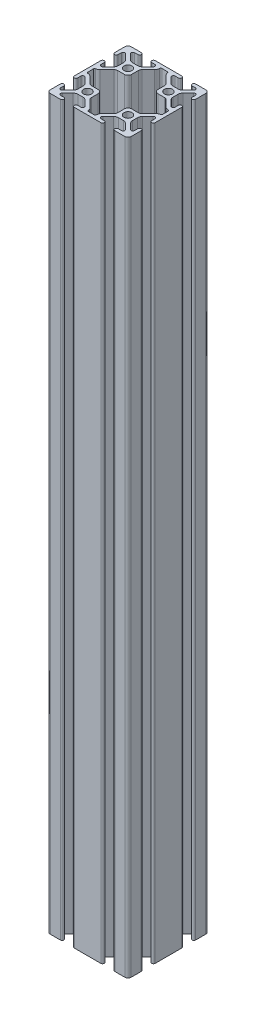
SolidWorks part; units mm, degrees
material "6061-T6 (SS)"
ref_plane "Front Plane" through (0, 0, 0) normal (0, 0, 1) x (1, 0, 0)
ref_plane "Top Plane" through (0, 0, 0) normal (0, 1, 0) x (1, 0, 0)
ref_plane "Right Plane" through (0, 0, 0) normal (1, 0, 0) x (0, 0, -1)
sketch "Sketch1" plane through (0, 0, 0) normal (0, 0, 1) x (1, 0, 0)
  line L0 (0, 0) -> (0, 450)
  dimension "D1" = 450
other "25 series extrusions 25-5050(1)"
ref_plane "Plane1" through (0, 0, 0) normal (0, 1, 0) x (-1, 0, 0)
sketch "Sketch13" plane through (0, 0, 0) normal (0, 1, 0) x (-1, 0, 0)
  line L0 (1.94, -22.8664) -> (-1.461, -22.8664)
  line L1 (-3.1194, -20.3719) -> (-7.4717, -16.0197)
  line L2 (-8.1189, -14.4571) -> (-8.1189, -10.3287)
  line L3 (-10.3287, -8.1189) -> (-14.4571, -8.1189)
  line L4 (-16.0197, -7.4717) -> (-19.8593, -3.632)
  line L5 (-22.8664, -1.94) -> (-22.8664, 1.461)
  line L6 (-20.3719, 3.1194) -> (-16.0197, 7.4717)
  line L7 (-14.4571, 8.1189) -> (-10.3287, 8.1189)
  line L8 (-8.1189, 10.3287) -> (-8.1189, 14.4571)
  line L9 (-7.4717, 16.0197) -> (-3.632, 19.8593)
  line L10 (-1.94, 22.8664) -> (1.461, 22.8664)
  line L11 (3.1194, 20.3719) -> (7.4717, 16.0197)
  line L12 (8.1189, 14.4571) -> (8.1189, 10.3287)
  line L13 (10.3287, 8.1189) -> (14.4571, 8.1189)
  line L14 (16.0197, 7.4717) -> (19.8593, 3.632)
  line L15 (22.8664, 1.94) -> (22.8664, -1.461)
  line L16 (20.3719, -3.1194) -> (16.0197, -7.4717)
  line L17 (14.4571, -8.1189) -> (10.3287, -8.1189)
  line L18 (8.1189, -10.3287) -> (8.1189, -14.4571)
  line L19 (7.4717, -16.0197) -> (3.632, -19.8593)
  line L20 (16.815, -25) -> (23, -25)
  line L21 (25, -23) -> (25, -16.815)
  line L22 (22.87, -16.815) -> (22.87, -18.7728)
  line L23 (21.0396, -19.531) -> (17.811, -16.3024)
  line L24 (16.8811, -14.0573) -> (16.8811, -10.9427)
  line L25 (17.811, -8.6976) -> (21.0396, -5.469)
  line L26 (22.87, -6.2272) -> (22.87, -8.185)
  line L27 (25, -8.185) -> (25, 8.185)
  line L28 (22.87, 8.185) -> (22.87, 6.2272)
  line L29 (21.0396, 5.469) -> (17.811, 8.6976)
  line L30 (16.8811, 10.9427) -> (16.8811, 14.0573)
  line L31 (17.811, 16.3024) -> (21.0396, 19.531)
  line L32 (22.87, 18.7728) -> (22.87, 16.815)
  line L33 (25, 16.815) -> (25, 23)
  line L34 (23, 25) -> (16.815, 25)
  line L35 (16.815, 22.87) -> (18.7728, 22.87)
  line L36 (19.531, 21.0396) -> (16.3024, 17.811)
  line L37 (14.0573, 16.8811) -> (10.9427, 16.8811)
  line L38 (8.6976, 17.811) -> (5.469, 21.0396)
  line L39 (6.2272, 22.87) -> (8.185, 22.87)
  line L40 (8.185, 25) -> (-8.185, 25)
  line L41 (-8.185, 22.87) -> (-6.2272, 22.87)
  line L42 (-5.469, 21.0396) -> (-8.6976, 17.811)
  line L43 (-10.9427, 16.8811) -> (-14.0573, 16.8811)
  line L44 (-16.3024, 17.811) -> (-19.531, 21.0396)
  line L45 (-18.7728, 22.87) -> (-16.815, 22.87)
  line L46 (-16.815, 25) -> (-23, 25)
  line L47 (-25, 23) -> (-25, 16.815)
  line L48 (-22.87, 16.815) -> (-22.87, 18.7728)
  line L49 (-21.0396, 19.531) -> (-17.811, 16.3024)
  line L50 (-16.8811, 14.0573) -> (-16.8811, 10.9427)
  line L51 (-17.811, 8.6976) -> (-21.0396, 5.469)
  line L52 (-22.87, 6.2272) -> (-22.87, 8.185)
  line L53 (-25, 8.185) -> (-25, -8.185)
  line L54 (-22.87, -8.185) -> (-22.87, -6.2272)
  line L55 (-21.0396, -5.469) -> (-17.811, -8.6976)
  line L56 (-16.8811, -10.9427) -> (-16.8811, -14.0573)
  line L57 (-17.811, -16.3024) -> (-21.0396, -19.531)
  line L58 (-22.87, -18.7728) -> (-22.87, -16.815)
  line L59 (-25, -16.815) -> (-25, -23)
  line L60 (-23, -25) -> (-16.815, -25)
  line L61 (-16.815, -22.87) -> (-18.7728, -22.87)
  line L62 (-19.531, -21.0396) -> (-16.3024, -17.811)
  line L63 (-14.0573, -16.8811) -> (-10.9427, -16.8811)
  line L64 (-8.6976, -17.811) -> (-5.469, -21.0396)
  line L65 (-6.2272, -22.87) -> (-8.185, -22.87)
  line L66 (-8.185, -25) -> (8.185, -25)
  line L67 (8.185, -22.87) -> (6.2272, -22.87)
  line L68 (5.469, -21.0396) -> (8.6976, -17.811)
  line L69 (10.9427, -16.8811) -> (14.0573, -16.8811)
  line L70 (16.3024, -17.811) -> (19.531, -21.0396)
  line L71 (18.7728, -22.87) -> (16.815, -22.87)
  circle A0 centre (12.5, 12.5) radius 2.5
  circle A1 centre (-12.5, -12.5) radius 2.5
  circle A2 centre (12.5, -12.5) radius 2.5
  circle A3 centre (-12.5, 12.5) radius 2.5
  arc A4 (1.94, -22.8664) -> (2.702, -22.1044) centre (1.94, -22.1044) ccw
  arc A5 (-2.2165, -22.2036) -> (-1.461, -22.8664) centre (-1.461, -22.1044) ccw
  arc A6 (-2.2165, -22.2036) -> (-3.1194, -20.3719) centre (-5.3645, -22.617) ccw
  arc A7 (-8.1189, -14.4571) -> (-7.4717, -16.0197) centre (-5.9091, -14.4571) ccw
  arc A8 (-8.1189, -10.3287) -> (-10.3287, -8.1189) centre (-10.3287, -10.3287) ccw
  arc A9 (-16.0197, -7.4717) -> (-14.4571, -8.1189) centre (-14.4571, -5.9091) ccw
  arc A10 (-19.8593, -3.632) -> (-22.1044, -2.702) centre (-22.1044, -5.877) ccw
  arc A11 (-22.8664, -1.94) -> (-22.1044, -2.702) centre (-22.1044, -1.94) ccw
  arc A12 (-22.2036, 2.2165) -> (-22.8664, 1.461) centre (-22.1044, 1.461) ccw
  arc A13 (-22.2036, 2.2165) -> (-20.3719, 3.1194) centre (-22.617, 5.3645) ccw
  arc A14 (-14.4571, 8.1189) -> (-16.0197, 7.4717) centre (-14.4571, 5.9091) ccw
  arc A15 (-10.3287, 8.1189) -> (-8.1189, 10.3287) centre (-10.3287, 10.3287) ccw
  arc A16 (-7.4717, 16.0197) -> (-8.1189, 14.4571) centre (-5.9091, 14.4571) ccw
  arc A17 (-3.632, 19.8593) -> (-2.702, 22.1044) centre (-5.877, 22.1044) ccw
  arc A18 (-1.94, 22.8664) -> (-2.702, 22.1044) centre (-1.94, 22.1044) ccw
  arc A19 (2.2165, 22.2036) -> (1.461, 22.8664) centre (1.461, 22.1044) ccw
  arc A20 (2.2165, 22.2036) -> (3.1194, 20.3719) centre (5.3645, 22.617) ccw
  arc A21 (8.1189, 14.4571) -> (7.4717, 16.0197) centre (5.9091, 14.4571) ccw
  arc A22 (8.1189, 10.3287) -> (10.3287, 8.1189) centre (10.3287, 10.3287) ccw
  arc A23 (16.0197, 7.4717) -> (14.4571, 8.1189) centre (14.4571, 5.9091) ccw
  arc A24 (19.8593, 3.632) -> (22.1044, 2.702) centre (22.1044, 5.877) ccw
  arc A25 (22.8664, 1.94) -> (22.1044, 2.702) centre (22.1044, 1.94) ccw
  arc A26 (22.2036, -2.2165) -> (22.8664, -1.461) centre (22.1044, -1.461) ccw
  arc A27 (22.2036, -2.2165) -> (20.3719, -3.1194) centre (22.617, -5.3645) ccw
  arc A28 (14.4571, -8.1189) -> (16.0197, -7.4717) centre (14.4571, -5.9091) ccw
  arc A29 (10.3287, -8.1189) -> (8.1189, -10.3287) centre (10.3287, -10.3287) ccw
  arc A30 (7.4717, -16.0197) -> (8.1189, -14.4571) centre (5.9091, -14.4571) ccw
  arc A31 (3.632, -19.8593) -> (2.702, -22.1044) centre (5.877, -22.1044) ccw
  arc A32 (23, -25) -> (25, -23) centre (23, -23) ccw
  arc A33 (25, -16.815) -> (22.87, -16.815) centre (23.935, -16.815) ccw
  arc A34 (21.0396, -19.531) -> (22.87, -18.7728) centre (21.7978, -18.7728) ccw
  arc A35 (16.8811, -14.0573) -> (17.811, -16.3024) centre (20.0561, -14.0573) ccw
  arc A36 (17.811, -8.6976) -> (16.8811, -10.9427) centre (20.0561, -10.9427) ccw
  arc A37 (22.87, -6.2272) -> (21.0396, -5.469) centre (21.7978, -6.2272) ccw
  arc A38 (22.87, -8.185) -> (25, -8.185) centre (23.935, -8.185) ccw
  arc A39 (25, 8.185) -> (22.87, 8.185) centre (23.935, 8.185) ccw
  arc A40 (21.0396, 5.469) -> (22.87, 6.2272) centre (21.7978, 6.2272) ccw
  arc A41 (16.8811, 10.9427) -> (17.811, 8.6976) centre (20.0561, 10.9427) ccw
  arc A42 (17.811, 16.3024) -> (16.8811, 14.0573) centre (20.0561, 14.0573) ccw
  arc A43 (22.87, 18.7728) -> (21.0396, 19.531) centre (21.7978, 18.7728) ccw
  arc A44 (22.87, 16.815) -> (25, 16.815) centre (23.935, 16.815) ccw
  arc A45 (25, 23) -> (23, 25) centre (23, 23) ccw
  arc A46 (16.815, 25) -> (16.815, 22.87) centre (16.815, 23.935) ccw
  arc A47 (19.531, 21.0396) -> (18.7728, 22.87) centre (18.7728, 21.7978) ccw
  arc A48 (14.0573, 16.8811) -> (16.3024, 17.811) centre (14.0573, 20.0561) ccw
  arc A49 (8.6976, 17.811) -> (10.9427, 16.8811) centre (10.9427, 20.0561) ccw
  arc A50 (6.2272, 22.87) -> (5.469, 21.0396) centre (6.2272, 21.7978) ccw
  arc A51 (8.185, 22.87) -> (8.185, 25) centre (8.185, 23.935) ccw
  arc A52 (-8.185, 25) -> (-8.185, 22.87) centre (-8.185, 23.935) ccw
  arc A53 (-5.469, 21.0396) -> (-6.2272, 22.87) centre (-6.2272, 21.7978) ccw
  arc A54 (-10.9427, 16.8811) -> (-8.6976, 17.811) centre (-10.9427, 20.0561) ccw
  arc A55 (-16.3024, 17.811) -> (-14.0573, 16.8811) centre (-14.0573, 20.0561) ccw
  arc A56 (-18.7728, 22.87) -> (-19.531, 21.0396) centre (-18.7728, 21.7978) ccw
  arc A57 (-16.815, 22.87) -> (-16.815, 25) centre (-16.815, 23.935) ccw
  arc A58 (-23, 25) -> (-25, 23) centre (-23, 23) ccw
  arc A59 (-25, 16.815) -> (-22.87, 16.815) centre (-23.935, 16.815) ccw
  arc A60 (-21.0396, 19.531) -> (-22.87, 18.7728) centre (-21.7978, 18.7728) ccw
  arc A61 (-16.8811, 14.0573) -> (-17.811, 16.3024) centre (-20.0561, 14.0573) ccw
  arc A62 (-17.811, 8.6976) -> (-16.8811, 10.9427) centre (-20.0561, 10.9427) ccw
  arc A63 (-22.87, 6.2272) -> (-21.0396, 5.469) centre (-21.7978, 6.2272) ccw
  arc A64 (-22.87, 8.185) -> (-25, 8.185) centre (-23.935, 8.185) ccw
  arc A65 (-25, -8.185) -> (-22.87, -8.185) centre (-23.935, -8.185) ccw
  arc A66 (-21.0396, -5.469) -> (-22.87, -6.2272) centre (-21.7978, -6.2272) ccw
  arc A67 (-16.8811, -10.9427) -> (-17.811, -8.6976) centre (-20.0561, -10.9427) ccw
  arc A68 (-17.811, -16.3024) -> (-16.8811, -14.0573) centre (-20.0561, -14.0573) ccw
  arc A69 (-22.87, -18.7728) -> (-21.0396, -19.531) centre (-21.7978, -18.7728) ccw
  arc A70 (-22.87, -16.815) -> (-25, -16.815) centre (-23.935, -16.815) ccw
  arc A71 (-25, -23) -> (-23, -25) centre (-23, -23) ccw
  arc A72 (-16.815, -25) -> (-16.815, -22.87) centre (-16.815, -23.935) ccw
  arc A73 (-19.531, -21.0396) -> (-18.7728, -22.87) centre (-18.7728, -21.7978) ccw
  arc A74 (-14.0573, -16.8811) -> (-16.3024, -17.811) centre (-14.0573, -20.0561) ccw
  arc A75 (-8.6976, -17.811) -> (-10.9427, -16.8811) centre (-10.9427, -20.0561) ccw
  arc A76 (-6.2272, -22.87) -> (-5.469, -21.0396) centre (-6.2272, -21.7978) ccw
  arc A77 (-8.185, -22.87) -> (-8.185, -25) centre (-8.185, -23.935) ccw
  arc A78 (8.185, -25) -> (8.185, -22.87) centre (8.185, -23.935) ccw
  arc A79 (5.469, -21.0396) -> (6.2272, -22.87) centre (6.2272, -21.7978) ccw
  arc A80 (10.9427, -16.8811) -> (8.6976, -17.811) centre (10.9427, -20.0561) ccw
  arc A81 (16.3024, -17.811) -> (14.0573, -16.8811) centre (14.0573, -20.0561) ccw
  arc A82 (18.7728, -22.87) -> (19.531, -21.0396) centre (18.7728, -21.7978) ccw
  arc A83 (16.815, -22.87) -> (16.815, -25) centre (16.815, -23.935) ccw
  point P0 (0, 0)
